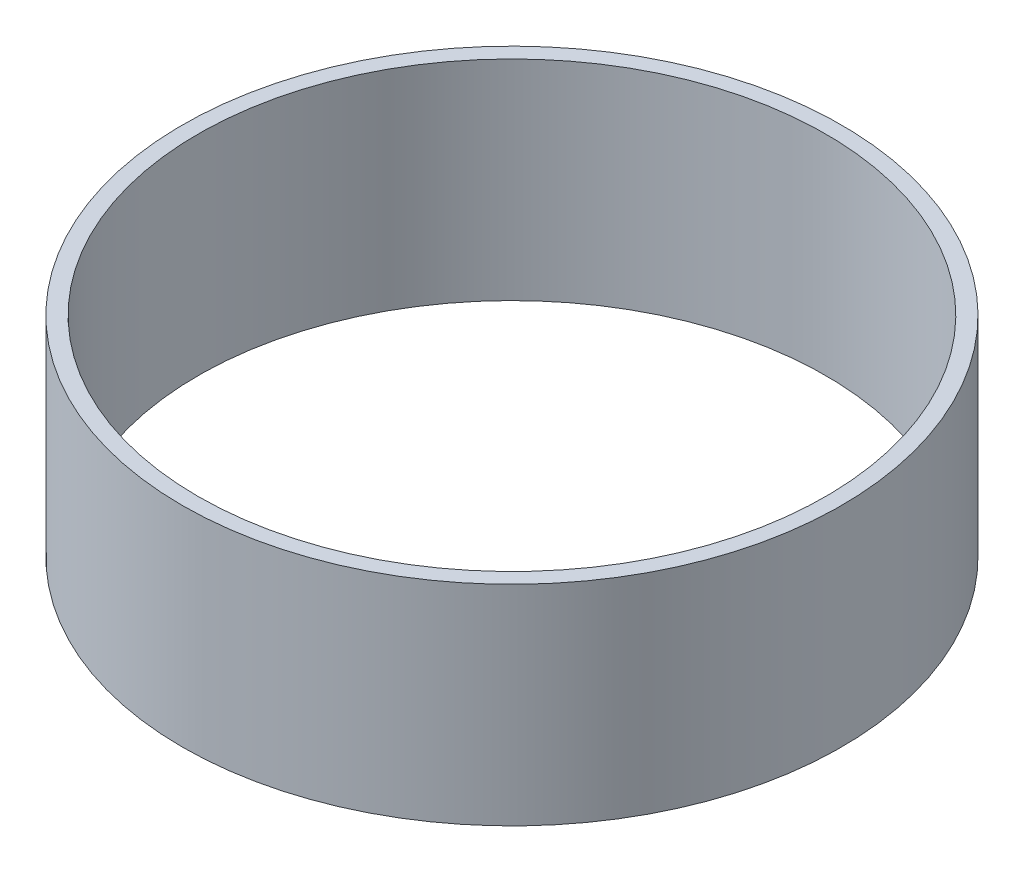
SolidWorks part; units mm, degrees
material "橡胶"
ref_plane "前视基准面" through (0, 0, 0) normal (0, 0, 1) x (1, 0, 0)
ref_plane "上视基准面" through (0, 0, 0) normal (0, 1, 0) x (1, 0, 0)
ref_plane "右视基准面" through (0, 0, 0) normal (1, 0, 0) x (0, 0, -1)
sketch "草图1" plane through (0, 0, 0) normal (0, 1, 0) x (1, 0, 0)
  circle A0 centre (0, 0) radius 63
  circle A1 centre (0, 0) radius 60
  dimension "D1" = 120
  dimension "D2" = 126
extrude "凸台-拉伸1" add sketch "草图1" along normal mid plane 40
